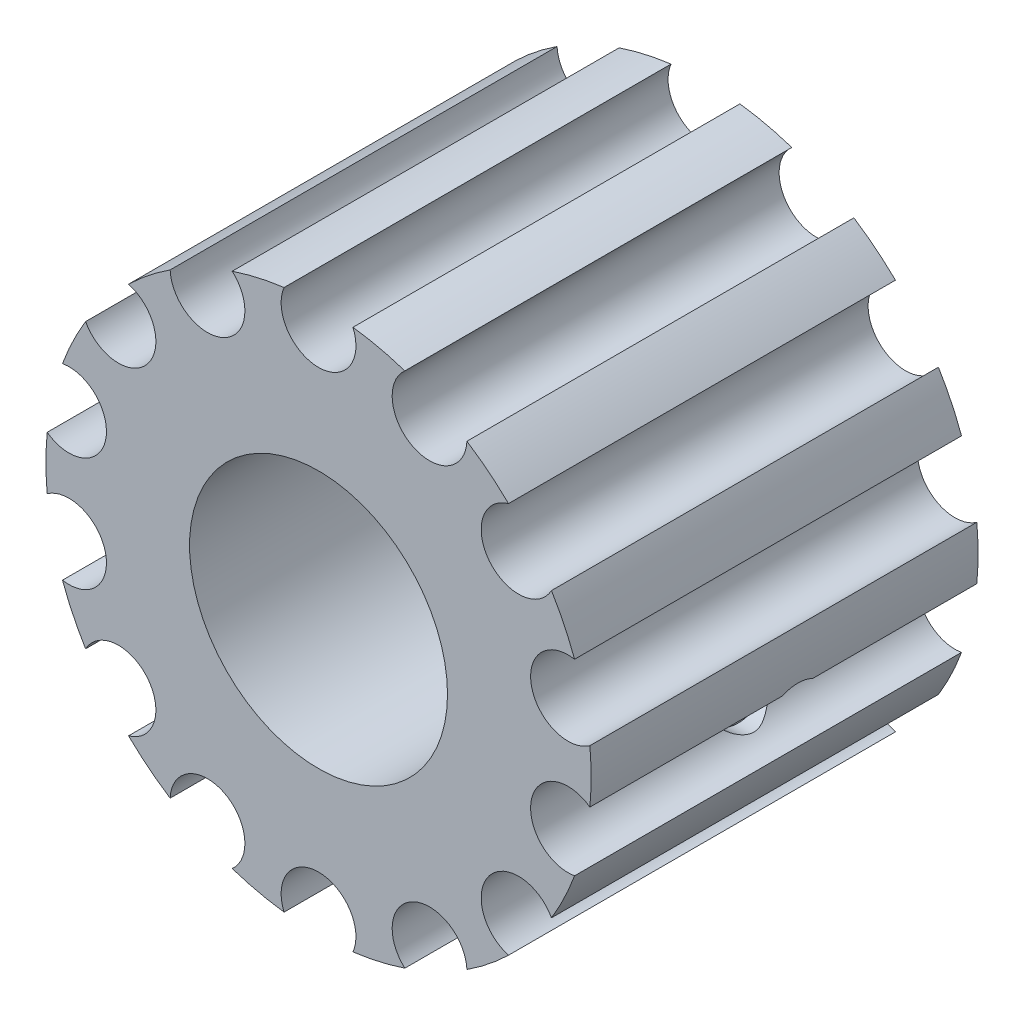
SolidWorks part; units mm, degrees
material "6061 Alloy"
ref_plane "Front Plane" through (0, 0, 0) normal (0, 0, 1) x (1, 0, 0)
ref_plane "Top Plane" through (0, 0, 0) normal (0, 1, 0) x (1, 0, 0)
ref_plane "Right Plane" through (0, 0, 0) normal (1, 0, 0) x (0, 0, -1)
sketch "Sketch1" plane through (0, 0, 0) normal (0, 0, 1) x (1, 0, 0)
  line L0 (0, 0) -> (0, 10.57) construction
  line L1 (0, 8.47) -> (11.5474, 8.47) construction
  line L2 (0, 9.92) -> (-8.106, 9.92) construction
  circle A0 centre (0, 0) radius 10.57
  circle A1 centre (0, 0) radius 8.47 construction
  circle A2 centre (0, 0) radius 9.92 construction
  circle A3 centre (0, 9.92) radius 1.45
  circle A4 centre (0, 0) radius 8.47 construction
  circle A5 centre (4.3041, 8.9376) radius 1.45
  circle A6 centre (0, 0) radius 8.47 construction
  circle A7 centre (7.7558, 6.185) radius 1.45
  circle A8 centre (0, 0) radius 8.47 construction
  circle A9 centre (9.6713, 2.2074) radius 1.45
  circle A10 centre (0, 0) radius 8.47 construction
  circle A11 centre (9.6713, -2.2074) radius 1.45
  circle A12 centre (0, 0) radius 8.47 construction
  circle A13 centre (7.7558, -6.185) radius 1.45
  circle A14 centre (0, 0) radius 8.47 construction
  circle A15 centre (4.3041, -8.9376) radius 1.45
  circle A16 centre (0, 0) radius 8.47 construction
  circle A17 centre (0, -9.92) radius 1.45
  circle A18 centre (0, 0) radius 8.47 construction
  circle A19 centre (-4.3041, -8.9376) radius 1.45
  circle A20 centre (0, 0) radius 8.47 construction
  circle A21 centre (-7.7558, -6.185) radius 1.45
  circle A22 centre (0, 0) radius 8.47 construction
  circle A23 centre (-9.6713, -2.2074) radius 1.45
  circle A24 centre (0, 0) radius 8.47 construction
  circle A25 centre (-9.6713, 2.2074) radius 1.45
  circle A26 centre (0, 0) radius 8.47 construction
  circle A27 centre (-7.7558, 6.185) radius 1.45
  circle A28 centre (0, 0) radius 8.47 construction
  circle A29 centre (-4.3041, 8.9376) radius 1.45
  circle A30 centre (0, 0) radius 5
  point P52 (0, 0)
  dimension "D1" = 21.14
  dimension "D4" = 16.94
  dimension "D6" = 10
  dimension "D2" = 2.1
  dimension "D3" = 0.65
  dimension "D5" = 14
extrude "Boss-Extrude1" add sketch "Sketch1" along normal blind 15 contours A29 A0 A27 A25 A23 A21 A19 A17 A15 A13 A11 A9 A7 A5 A3
sketch "Sketch2" plane through (0, 0, 15) normal (0, 0, 1) x (1, 0, 0)
  circle A0 centre (0, 0) radius 12.5
  circle A1 centre (0, 0) radius 10.57
  circle A3 centre (0, 0) radius 5
  circle A4 centre (0, 0) radius 5
  circle A5 centre (4.3041, 8.9376) radius 1.45
  circle A6 centre (4.3041, 8.9376) radius 1.45
  circle A7 centre (0, 9.92) radius 1.45
  circle A8 centre (0, 9.92) radius 1.45
  circle A9 centre (0, 0) radius 10.57
  circle A10 centre (0, 0) radius 10.57
  circle A11 centre (4.3041, -8.9376) radius 1.45
  circle A12 centre (4.3041, -8.9376) radius 1.45
  circle A13 centre (7.7558, -6.185) radius 1.45
  circle A14 centre (7.7558, -6.185) radius 1.45
  circle A15 centre (9.6713, -2.2074) radius 1.45
  circle A16 centre (9.6713, -2.2074) radius 1.45
  circle A17 centre (9.6713, 2.2074) radius 1.45
  circle A18 centre (9.6713, 2.2074) radius 1.45
  circle A19 centre (7.7558, 6.185) radius 1.45
  circle A20 centre (7.7558, 6.185) radius 1.45
  circle A21 centre (-9.6713, 2.2074) radius 1.45
  circle A22 centre (-9.6713, 2.2074) radius 1.45
  circle A23 centre (-9.6713, -2.2074) radius 1.45
  circle A24 centre (-9.6713, -2.2074) radius 1.45
  circle A25 centre (-7.7558, -6.185) radius 1.45
  circle A26 centre (-7.7558, -6.185) radius 1.45
  circle A27 centre (-4.3041, -8.9376) radius 1.45
  circle A28 centre (-4.3041, -8.9376) radius 1.45
  circle A29 centre (0, -9.92) radius 1.45
  circle A30 centre (0, -9.92) radius 1.45
  circle A31 centre (-4.3041, 8.9376) radius 1.45
  circle A32 centre (-4.3041, 8.9376) radius 1.45
  circle A33 centre (-7.7558, 6.185) radius 1.45
  circle A34 centre (-7.7558, 6.185) radius 1.45
  dimension "D1" = 25
  dimension "D2" = 0
  dimension "D3" = 0
  dimension "D4" = 0
  dimension "D5" = 0
  dimension "D6" = 0
  dimension "D7" = 0
  dimension "D8" = 0
  dimension "D9" = 0
  dimension "D10" = 0
  dimension "D11" = 0
  dimension "D12" = 0
  dimension "D13" = 0
  dimension "D14" = 0
  dimension "D15" = 0
  dimension "D16" = 0
  dimension "D17" = 0
ref_plane "Plane1" through (8.2213, 0, 0) normal (1, 0, 0) x (0, 0, -1)
hole_wizard "M3 Tapped Hole1" positions "Sketch6" profile "Sketch7" tap size "M3" standard "ISO"
sketch "Sketch6" plane through (8.2213, 0, 0) normal (1, 0, 0) x (0, 0, -1)
  line L0 (-10, -2.135) -> (-3.9, -2.135) construction
  line L3 (-15, 3.6574) -> (-15, 0.7574) construction
  line L4 (-15, -3.635) -> (0, -3.635) construction
  point P0 (-6.95, -2.135)
  point P10 (-6.95, -2.135)
  dimension "D1" = 5
  dimension "D2" = 1.5
sketch "Sketch7" plane through (8.2213, -2.135, 6.95) normal (0, 1, 0) x (0, 0, 1)
  line L0 (0, 0) -> (0, 2.3487)
  line L1 (0, 2.3487) -> (1.25, 2.3487)
  line L2 (1.25, 2.3487) -> (1.25, 0)
  line L5 (1.25, 0) -> (0, 0)
  line L11 (0, -6.35) -> (0, 107.95) construction
  dimension "Thread Major Dia." = 2.5
  dimension "Thru Tap Drill Depth" = 2.3487
